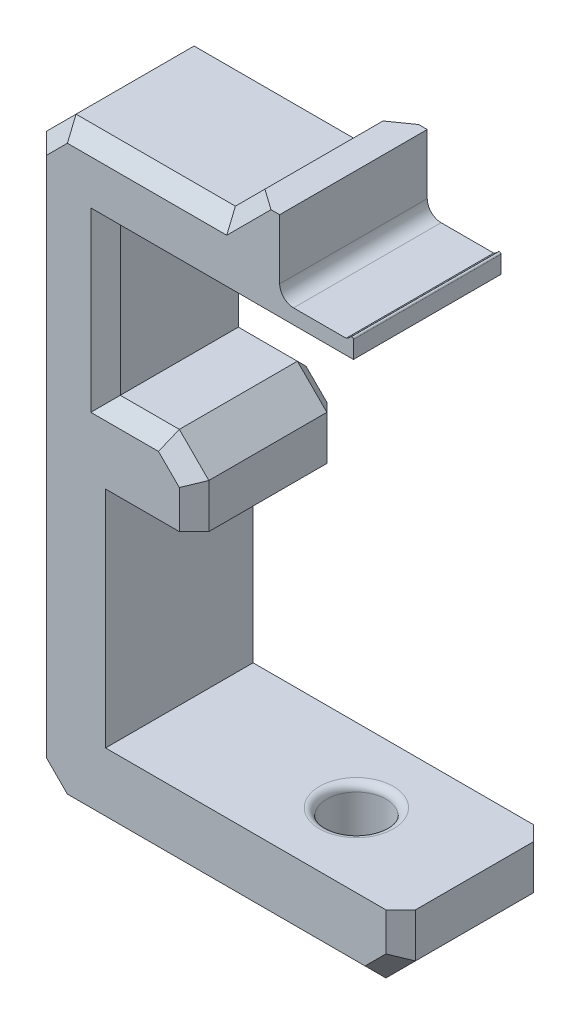
SolidWorks part; units mm, degrees
ref_plane "Plano frontal" through (0, 0, 0) normal (0, 0, 1) x (1, 0, 0)
ref_plane "Plano superior" through (0, 0, 0) normal (0, 1, 0) x (1, 0, 0)
ref_plane "Plano direito" through (0, 0, 0) normal (1, 0, 0) x (0, 0, -1)
sketch "Esboço1" plane through (0, 0, 0) normal (0, 0, 1) x (1, 0, 0)
  line L0 (11, 14.25) -> (-5.8, 14.25)
  line L1 (0.2, -0.75) -> (-5.8, -0.75)
  line L2 (-5.8, 14.25) -> (-5.8, 4.25)
  line L3 (-5.8, -15.95) -> (14.2, -15.95)
  line L4 (14.2, -15.95) -> (14.2, -20.95)
  line L5 (14.2, -20.95) -> (-10.8, -20.95)
  line L6 (-10.8, -20.95) -> (-10.8, 19.25)
  line L7 (0.2, 4.25) -> (0.2, -0.75)
  line L8 (0.2, 4.25) -> (-5.8, 4.25)
  line L9 (-5.8, -0.75) -> (-5.8, -15.95)
  line L10 (11, 14.25) -> (11, 16.25)
  line L11 (10.5044, 16.25) -> (6, 16.25)
  line L12 (6, 16.25) -> (6, 19.25)
  line L13 (6, 19.25) -> (-10.8, 19.25)
  line L14 (11, 16.25) -> (11, 16.4263)
  arc A0 (11, 16.4263) -> (10.8262, 16.4939) centre (10.9, 16.4263) ccw
  arc A1 (10.5044, 16.25) -> (10.8262, 16.4939) centre (10, 17.25) ccw
  dimension "D12" = 0.1
  dimension "D1" = 5
  dimension "D2" = 20
  dimension "D3" = 15.2
  dimension "D4" = 6
  dimension "D5" = 5
  dimension "D6" = 5
  dimension "D7" = 2
  dimension "D8" = 5
  dimension "D9" = 10
  dimension "D10" = 16.8
  dimension "D11" = 5
  dimension "D13" = 0.1763
  dimension "D14" = 0.4956
extrude "Ressalto-extrusão1" add sketch "Esboço1" along normal blind 10
sketch "Esboço3" plane through (0, -20.95, 0) normal (0, -1, 0) x (1, 0, 0)
  line L0 (14.2, 5) -> (6.2, 5) construction
  line L1 (14.2, 10) -> (14.2, 0) construction
  circle A0 centre (6.2, 5) radius 2
  dimension "D1" = 4
  dimension "D2" = 8
extrude "Corte-extrusão1" cut sketch "Esboço3" against normal blind 15
chamfer "Chanfro1" distance 1.6 angle 45 1 edges at (6.2, -20.95, 3)
fillet "Filete1" radius 0.5 1 edges at (8.2, -15.95, 5)
fillet "Filete2" radius 0.94 1 edges at (6, 16.25, 5)
sketch "Esboço5" plane through (0, 0, 10) normal (0, 0, 1) x (1, 0, 0)
  line L0 (6, 19.25) -> (6, 21.25)
  line L1 (6, 21.25) -> (4, 21.25)
  line L2 (4, 21.25) -> (2, 19.25)
  line L3 (6, 19.25) -> (-10.8, 19.25) construction
  line L4 (2, 19.25) -> (6, 19.25)
  dimension "D1" = 135
  dimension "D2" = 2
  dimension "D3" = 2
extrude "Ressalto-extrusão3" add sketch "Esboço5" against normal up to surface (10 mm away) up to face at (2.7124, 4.8624, 0)
chamfer "Chanfro5" distance 2 angle 45 4 edges at (14.2, -20.95, 5) (-10.8, -20.95, 5) (-10.8, 19.25, 5) (0.2, 4.25, 5)
chamfer "Chanfro4" distance 1 angle 45 27 edges at (-5.8, 9.25, 0) (-5.8, 9.25, 10) (2.6, 14.25, 0) (2.6, 14.25, 10) (11, 14.25, 5) (-3.8, 4.25, 0) (-3.8, 4.25, 10) (3, 20.25, 0) (3, 20.25, 10) (-3.4, 19.25, 0) (-9.8, 18.25, 0) (-10.8, -0.85, 0) (-9.8, -19.95, 0) (1.7, -20.95, 0) (13.2, -19.95, 0) (14.2, -17.45, 0) (-3.4, 19.25, 10) (-9.8, 18.25, 10) (-10.8, -0.85, 10) (-9.8, -19.95, 10) (1.7, -20.95, 10) (13.2, -19.95, 10) (14.2, -17.45, 10) (0.2, 0.75, 0) (-0.8, 3.25, 0) (0.2, 0.75, 10) (-0.8, 3.25, 10)
